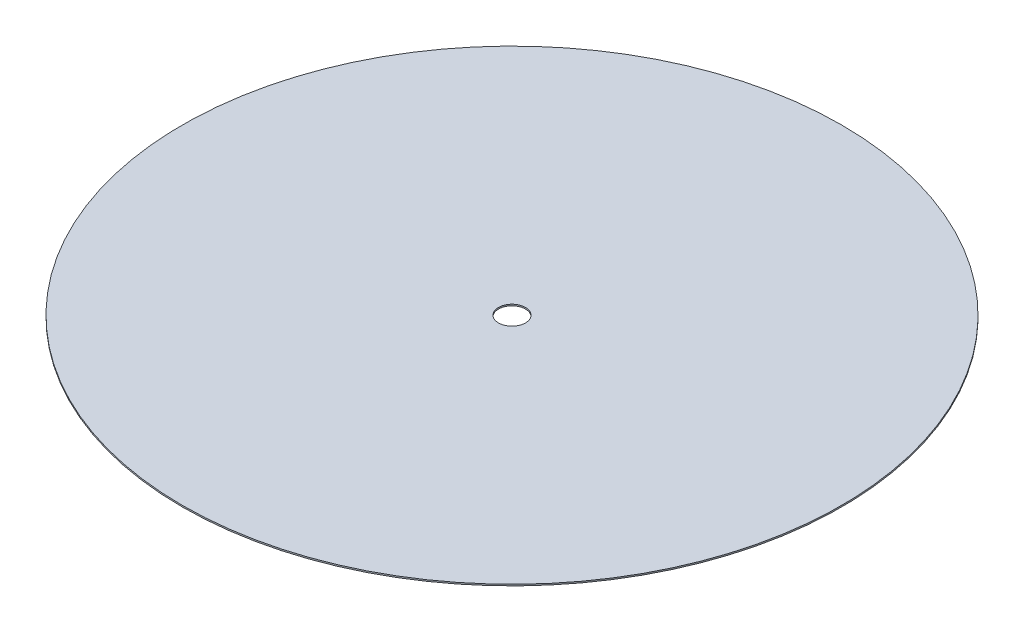
SolidWorks part; units mm, degrees
material "SlipDisc"
ref_plane "Front Plane" through (0, 0, 0) normal (0, 0, 1) x (1, 0, 0)
ref_plane "Top Plane" through (0, 0, 0) normal (0, 1, 0) x (1, 0, 0)
ref_plane "Right Plane" through (0, 0, 0) normal (1, 0, 0) x (0, 0, -1)
sketch "Sketch1" plane through (0, 0, 0) normal (0, 1, 0) x (1, 0, 0)
  circle A0 centre (0, 0) radius 160.3375
  dimension "D1" = 320.675
extrude "Boss-Extrude1" add sketch "Sketch1" along normal blind 0.7
sketch "Sketch2" plane through (0, 0.7, 0) normal (0, 1, 0) x (1, 0, 0)
  circle A0 centre (0, 0) radius 6.55
  dimension "D1" = 13.1
extrude "Cut-Extrude1" cut sketch "Sketch2" against normal through all
